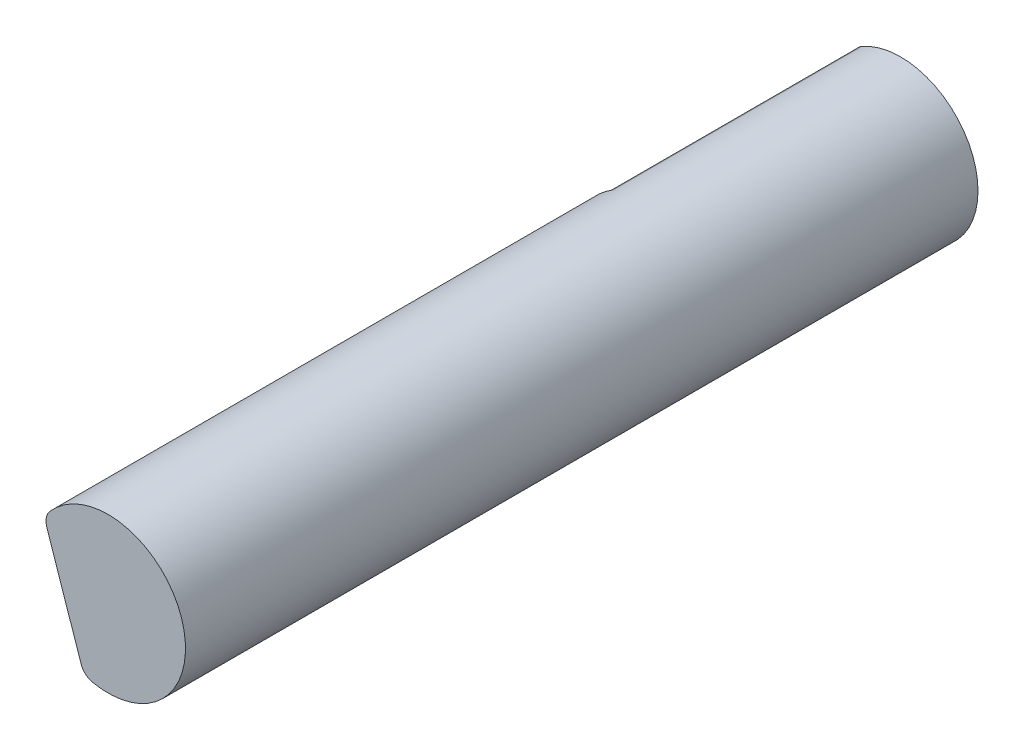
SolidWorks part; units mm, degrees
material "Plain Carbon Steel"
ref_plane "Front Plane" through (0, 0, 0) normal (0, 0, 1) x (1, 0, 0)
ref_plane "Top Plane" through (0, 0, 0) normal (0, 1, 0) x (1, 0, 0)
ref_plane "Right Plane" through (0, 0, 0) normal (1, 0, 0) x (0, 0, -1)
sketch "Sketch1" plane through (0, 0, 0) normal (0, 0, 1) x (1, 0, 0)
  circle A0 centre (0, 0) radius 4.98
  dimension "D1" = 9.96
extrude "Boss-Extrude1" add sketch "Sketch1" along normal blind 50
sketch "Sketch2" plane through (0, 0, 0) normal (0, 0, -1) x (-1, 0, 0)
  line L0 (3, 3.975) -> (3, -3.975)
  circle A1 centre (0, 0) radius 4.98
  circle A2 centre (0, 0) radius 4.98
  circle M3 centre (0, 0) radius 4.98
  dimension "D2" = 3
  dimension "D1" = 0
extrude "Cut-Extrude1" cut sketch "Sketch2" against normal blind 16 contours L0 M3 | A2
sketch "Sketch3" plane through (0, 0, 50) normal (0, 0, 1) x (1, 0, 0)
  line L0 (-4.98, 0) -> (0, 0) construction
  line L1 (0, 0) -> (-4.7181, -1.5936) construction
  line L2 (10.0387, 20.2787) -> (20.2787, -10.0387) construction
  line L3 (20.2787, -10.0387) -> (-104.7804, -52.2787) construction
  line L4 (-104.7804, -52.2787) -> (-115.0204, -21.9613) construction
  line L5 (-115.0204, -21.9613) -> (10.0387, 20.2787) construction
  line L6 (15.1587, 5.12) -> (-109.9004, -37.12) construction
  line L7 (-4.1223, 2.8297) -> (-1.5623, -4.7497)
  circle A0 centre (0, 0) radius 4.98 construction
  circle A1 centre (0, 0) radius 5
  circle A2 centre (0, 0) radius 4.98
  circle A3 centre (0, 0) radius 4.98
  circle A4 centre (-94.7418, -32) radius 5 construction
  circle M11 centre (0, 0) radius 4.98
  dimension "D2" = 16
  dimension "D6" = 10
  dimension "D7" = 32
  dimension "D1" = 0
  dimension "D3" = 16
  dimension "D4" = 132
  dimension "D5" = 32
  dimension "D8" = 3
extrude "Cut-Extrude2" cut sketch "Sketch3" against normal blind 16 contours L7 M11
fillet "Fillet1" radius 1 4 edges at (-4.1142, 2.806, 42) (-1.5703, -4.726, 42) (-3, -3.975, 8) (-3, 3.975, 8)
sketch "Sketch4" plane through (0, 0, 50) normal (0, 0, 1) x (1, 0, 0)
  line L1 (-3.9434, 2.3001) -> (-1.7411, -4.2201)
  line L2 (-3.9434, 2.3001) -> (-1.7411, -4.2201)
  arc A3 (-0.9931, -4.88) -> (-3.7487, 3.2784) centre (0, 0) ccw
  arc A4 (-3.7487, 3.2784) -> (-3.9434, 2.3001) centre (-2.996, 2.6201) ccw
  arc A5 (-1.7411, -4.2201) -> (-0.9931, -4.88) centre (-0.7937, -3.9001) ccw
  arc A6 (-0.9931, -4.88) -> (-3.7487, 3.2784) centre (0, 0) ccw
  arc A7 (-3.7487, 3.2784) -> (-3.9434, 2.3001) centre (-2.996, 2.6201) ccw
  arc A8 (-1.7411, -4.2201) -> (-0.9931, -4.88) centre (-0.7937, -3.9001) ccw
  dimension "D1" = 0
extrude "Boss-Extrude2" add sketch "Sketch4" along normal blind 1
sketch "Sketch5" plane through (0, 0, 51) normal (0, 0, 1) x (1, 0, 0)
  line L0 (0, 4.98) -> (0, 0) construction
  line L1 (0, 0) -> (-2.8423, -0.96) construction
  line L2 (-3.9434, 2.3001) -> (-1.7411, -4.2201) construction
  arc A0 (-0.9931, -4.88) -> (-3.7487, 3.2784) centre (0, 0) ccw construction
